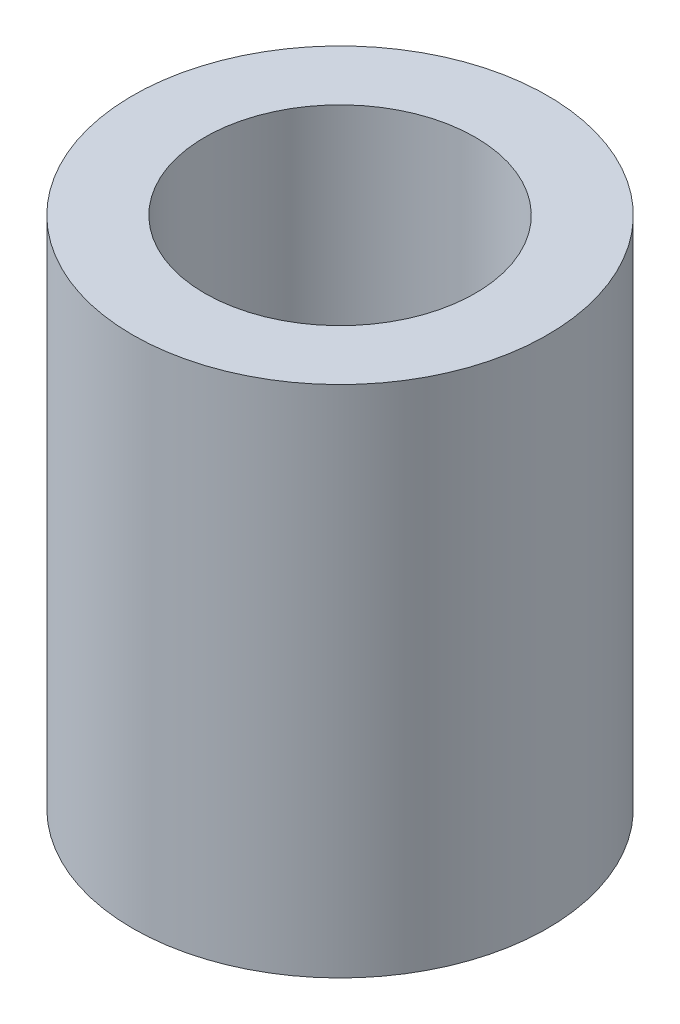
SolidWorks part; units mm, degrees
ref_plane "Front Plane" through (0, 0, 0) normal (0, 0, 1) x (1, 0, 0)
ref_plane "Top Plane" through (0, 0, 0) normal (0, 1, 0) x (1, 0, 0)
ref_plane "Right Plane" through (0, 0, 0) normal (1, 0, 0) x (0, 0, -1)
sketch "Sketch1" plane through (0, 0, 0) normal (0, 1, 0) x (1, 0, 0)
  circle A0 centre (0, 0) radius 2.3
  circle A1 centre (0, 0) radius 1.5
  dimension "D1" = 3
  dimension "D2" = 4.6
extrude "Boss-Extrude1" add sketch "Sketch1" along normal blind 5.7
